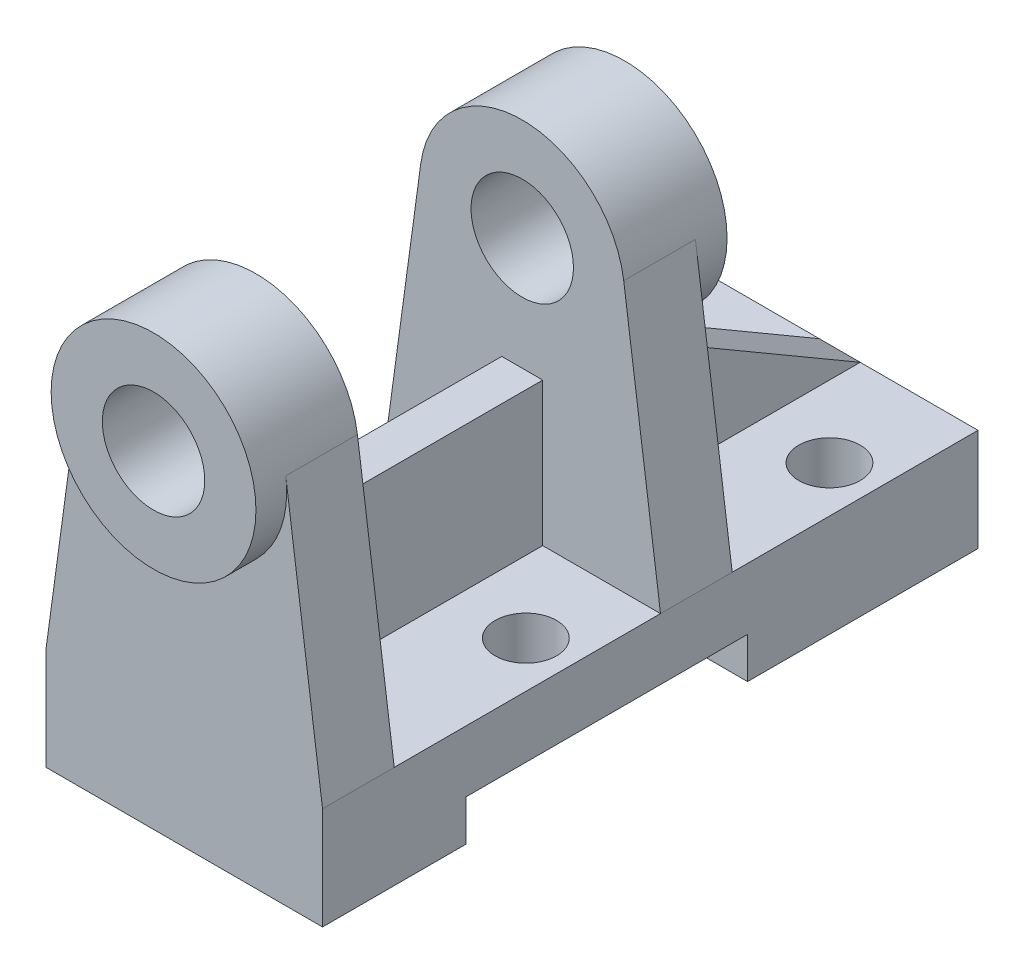
SolidWorks part; units mm, degrees
ref_plane "Front Plane" through (0, 0, 0) normal (0, 0, 1) x (1, 0, 0)
ref_plane "Top Plane" through (0, 0, 0) normal (0, 1, 0) x (1, 0, 0)
ref_plane "Right Plane" through (0, 0, 0) normal (1, 0, 0) x (0, 0, -1)
sketch "Sketch1" plane through (0, 0, 0) normal (1, 0, 0) x (0, 0, -1)
  line L0 (0, 0) -> (0, 20)
  line L1 (0, 20) -> (128, 20)
  line L2 (128, 20) -> (128, 0)
  line L3 (128, 0) -> (83, 0)
  line L4 (83, 0) -> (83, 8)
  line L5 (83, 8) -> (28, 8)
  line L6 (28, 8) -> (28, 0)
  line L7 (28, 0) -> (0, 0)
  dimension "D1" = 128
  dimension "D2" = 20
  dimension "D3" = 55
  dimension "D4" = 8
  dimension "D5" = 45
extrude "Boss-Extrude1" add sketch "Sketch1" along normal mid plane 54
sketch "Sketch2" plane through (0, 0, 0) normal (0, 0, 1) x (1, 0, 0)
  circle A0 centre (0, 70) radius 20
  point P6 (0, 0)
  dimension "D1" = 40
  dimension "D2" = 70
extrude "Boss-Extrude2" add sketch "Sketch2" along normal blind 6 and the other way blind 14 separate body contours A0
sketch "Sketch3" plane through (0, 0, 6) normal (0, 0, 1) x (1, 0, 0)
  line L0 (27, 20) -> (-27, 20) construction
  line L1 (27, 20) -> (-27, 20)
  line L2 (-19.8168, 72.7011) -> (-27, 20)
  line L3 (19.8168, 72.7011) -> (27, 20)
  circle A0 centre (0, 70) radius 20 construction
  arc A1 (-19.8168, 72.7011) -> (19.8168, 72.7011) centre (0, 70) ccw
extrude "Boss-Extrude3" add sketch "Sketch3" against normal blind 14 from offset 6 offset against normal yes
ref_plane "Plane1" through (0, 0, -66) normal (0, 0, 1) x (1, 0, 0)
sketch "Sketch4" plane through (0, 0, -66) normal (0, 0, 1) x (1, 0, 0)
  line L0 (-27, 20) -> (27, 20) construction
  line L1 (-27, 20) -> (27, 20)
  line L2 (27, 20) -> (19.8168, 72.7011) construction
  line L3 (-19.8168, 72.7011) -> (-27, 20) construction
  line L4 (27, 20) -> (19.8168, 72.7011)
  line L5 (-19.8168, 72.7011) -> (-27, 20)
  arc A0 (19.8168, 72.7011) -> (-19.8168, 72.7011) centre (0, 70) ccw construction
  arc A1 (19.8168, 72.7011) -> (-19.8168, 72.7011) centre (0, 70) ccw
extrude "Boss-Extrude4" add sketch "Sketch4" against normal blind 14
sketch "Sketch5" plane through (0, 0, -66) normal (0, 0, 1) x (1, 0, 0)
  circle A0 centre (0, 70) radius 20
  dimension "D1" = 40
extrude "Boss-Extrude5" add sketch "Sketch5" against normal blind 20
hole_wizard "Hole1" positions "Sketch6" profile "Sketch7" legacy end condition through all
sketch "Sketch6" plane through (0, 0, 6) normal (0, 0, 1) x (1, 0, 0)
  point P0 (0, 70)
sketch "Sketch7" plane through (0, 70, 6) normal (1, 0, 0) x (0, -1, 0)
  line L0 (0, 0) -> (0, 134)
  line L1 (0, 134) -> (10, 134)
  line L2 (10, 134) -> (10, 0)
  line L3 (10, 0) -> (0, 0)
  line L4 (0, 110) -> (0, -10) construction
  dimension "Diameter" = 20
  dimension "Depth" = 134
sketch "Sketch8" plane through (0, 0, 0) normal (1, 0, 0) x (0, 0, -1)
  line L0 (14, 48) -> (66, 48)
  line L3 (66, 48) -> (66, 20)
  line L4 (66, 20) -> (14, 20)
  line L5 (14, 20) -> (14, 48)
  dimension "D1" = 28
extrude "Boss-Extrude6" add sketch "Sketch8" along normal mid plane 8
sketch "Sketch9" plane through (0, 0, 0) normal (1, 0, 0) x (0, 0, -1)
  line L0 (80, 48) -> (128, 20)
  line L1 (80, 20) -> (80, 72.7011) construction
  line L2 (128, 20) -> (80, 20)
  line L3 (128, 20) -> (80, 20) construction
  line L4 (80, 20) -> (80, 48)
  dimension "D1" = 28
extrude "Boss-Extrude7" add sketch "Sketch9" along normal mid plane 8
hole_wizard "Hole2" positions "Sketch10" profile "Sketch11" legacy end condition through all
sketch "Sketch10" plane through (0, 20, 0) normal (0, 1, 0) x (1, 0, 0)
  line L0 (0, 0) -> (0, 149.0023) construction
  line L2 (27, 128) -> (4, 128) construction
  point P0 (18, 108)
  point P2 (-18, 108)
  point P10 (0, 0)
  dimension "D1" = 36
  dimension "D2" = 20
sketch "Sketch11" plane through (18, 20, -108) normal (1, 0, 0) x (0, 0, 1)
  line L0 (0, 0) -> (0, 20)
  line L1 (0, 20) -> (6, 20)
  line L2 (6, 20) -> (6, 0)
  line L3 (6, 0) -> (0, 0)
  line L4 (0, 110) -> (0, -10) construction
  dimension "Diameter" = 12
  dimension "Depth" = 20
pattern_linear "LPattern1" count 2 spacing 59.3 along (0, 0, 1) of "Hole2"
